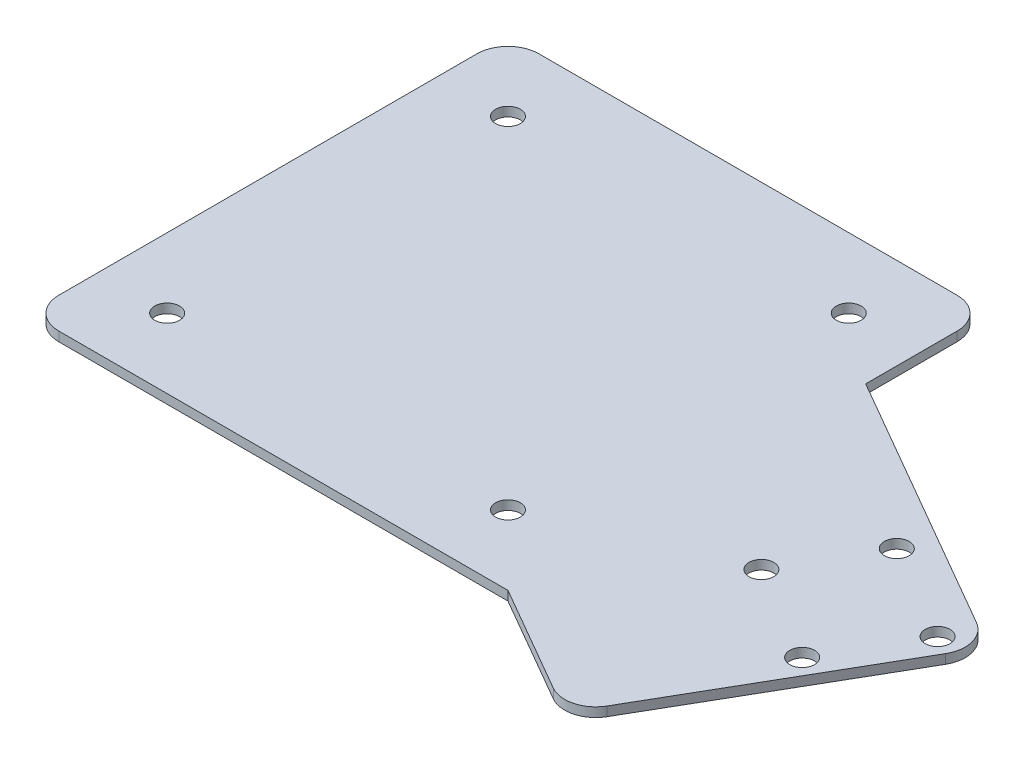
SolidWorks part; units mm, degrees
ref_plane "Płaszczyzna przednia" through (0, 0, 0) normal (0, 0, 1) x (1, 0, 0)
ref_plane "Płaszczyzna górna" through (0, 0, 0) normal (0, 1, 0) x (1, 0, 0)
ref_plane "Płaszczyzna prawa" through (0, 0, 0) normal (1, 0, 0) x (0, 0, -1)
sketch "Szkic1" plane through (0, 0, 0) normal (0, 1, 0) x (1, 0, 0)
  line L0 (77.5, -77.5) -> (120.8013, -102.5)
  line L1 (77.5, -77.5) -> (-77.5, -77.5)
  line L2 (77.5, 37.9701) -> (77.5, 77.5)
  line L3 (77.5, 77.5) -> (-77.5, 77.5)
  line L4 (-77.5, -77.5) -> (-77.5, 77.5)
  line L5 (0, 155.5335) -> (0, -127.0193) construction
  line L6 (-190.441, 0) -> (257.1583, 0) construction
  line L7 (120.8013, -102.5) -> (170.8013, -15.8975)
  line L8 (170.8013, -15.8975) -> (77.5, 37.9701)
  line L10 (77.5, 37.9701) -> (77.5, -159.42) construction
  line L11 (99.1506, -90) -> (166.7249, 27.0421) construction
  line L12 (145.8013, -59.1987) -> (103.634, -34.8535) construction
  line L13 (159.7391, -21.0577) -> (143.7391, -48.7705) construction
  circle A4 centre (-55, 55) radius 4
  circle A5 centre (55, 55) radius 4
  circle A6 centre (55, -55) radius 4
  circle A7 centre (-55, -55) radius 4
  circle A10 centre (159.7391, -21.0577) radius 4
  circle A11 centre (143.7391, -48.7705) radius 4
  circle A12 centre (128.5622, -3.0577) radius 4
  circle A13 centre (112.5622, -30.7705) radius 4
  point P0 (0, 0)
  point P6 (0, 77.5)
  point P7 (-77.5, 0)
  point P26 (0, 0)
  dimension "D4" = 8
  dimension "D5" = 110
  dimension "D6" = 4
  dimension "D7" = 7
  dimension "D12" = 8
  dimension "D13" = 8
  dimension "D1" = 155
  dimension "D2" = 155
  dimension "D3" = 110
  dimension "D8" = 100
  dimension "D9" = 30
  dimension "D10" = 50
  dimension "D11" = 10
  dimension "D14" = 8
extrude "Dodanie-wyciągnięcie1" add sketch "Szkic1" along normal blind 3
fillet "Zaokrąglenie1" radius 10 5 edges at (120.8013, 1.5, 102.5) (170.8013, 1.5, 15.8975) (77.5, 1.5, -77.5) (-77.5, 1.5, -77.5) (-77.5, 1.5, 77.5)
